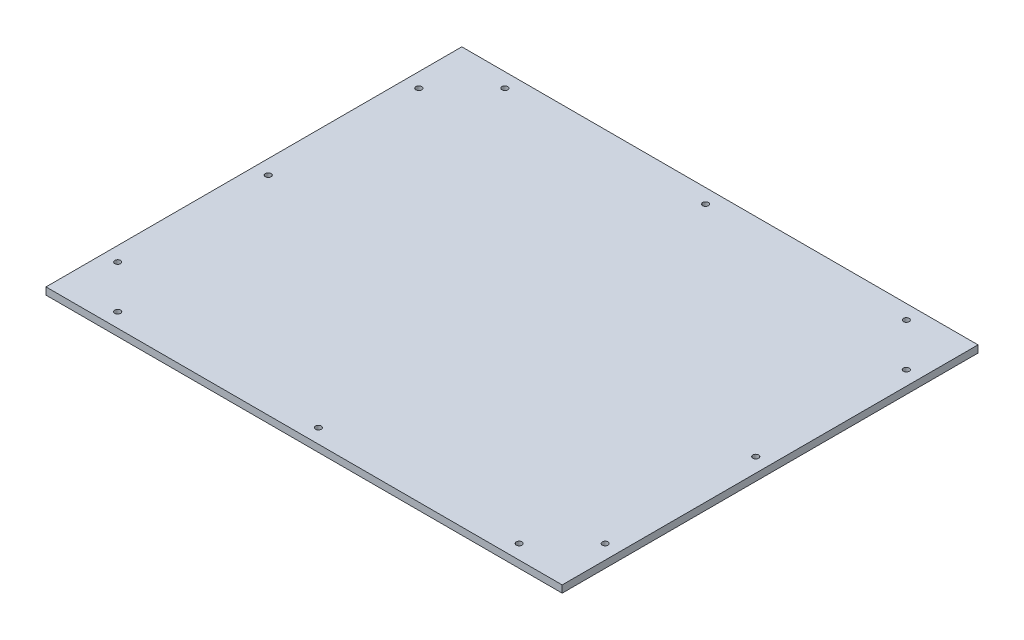
SolidWorks part; units mm, degrees
ref_plane "Front Plane" through (0, 0, 0) normal (0, 0, 1) x (1, 0, 0)
ref_plane "Top Plane" through (0, 0, 0) normal (0, 1, 0) x (1, 0, 0)
ref_plane "Right Plane" through (0, 0, 0) normal (1, 0, 0) x (0, 0, -1)
sketch "Sketch1" plane through (0, 0, 0) normal (0, 1, 0) x (1, 0, 0)
  line L0 (228.6, 368.3) -> (228.6, 0) construction
  line L1 (0, 0) -> (457.2, 0)
  line L2 (0, 0) -> (0, 368.3)
  line L3 (0, 368.3) -> (457.2, 368.3)
  line L4 (457.2, 0) -> (457.2, 368.3)
  line L6 (444.5, 12.7) -> (12.7, 12.7) construction
  line L7 (444.5, 12.7) -> (444.5, 355.6) construction
  line L8 (444.5, 355.6) -> (12.7, 355.6) construction
  line L9 (12.7, 12.7) -> (12.7, 355.6) construction
  line L10 (444.5, 12.7) -> (12.7, 355.6) construction
  line L11 (444.5, 355.6) -> (12.7, 12.7) construction
  circle A0 centre (50.8, 355.6) radius 2.5527
  circle A1 centre (406.4, 355.6) radius 2.5527
  circle A2 centre (406.4, 12.7) radius 2.5527
  circle A3 centre (50.8, 12.7) radius 2.5527
  circle A4 centre (228.6, 12.7) radius 2.5527
  circle A5 centre (228.6, 355.6) radius 2.5527
  circle A6 centre (12.7, 184.15) radius 2.5527
  circle A7 centre (444.5, 184.15) radius 2.5527
  circle A8 centre (12.7, 50.8) radius 2.5527
  circle A9 centre (444.5, 50.8) radius 2.5527
  circle A10 centre (444.5, 317.5) radius 2.5527
  circle A11 centre (12.7, 317.5) radius 2.5527
  point P7 (228.6, 184.15)
  dimension "D5" = 5.1054
  dimension "D6" = 5.1054
  dimension "D7" = 50.8
  dimension "D8" = 5.1054
  dimension "D9" = 5.1054
  dimension "D10" = 50.8
  dimension "D11" = 5.1054
  dimension "D12" = 5.1054
  dimension "D13" = 5.1054
  dimension "D15" = 5.1054
  dimension "D18" = 5.1054
  dimension "D19" = 5.1054
  dimension "D21" = 5.1054
  dimension "D23" = 5.1054
  dimension "D1" = 457.2
  dimension "D2" = 368.3
  dimension "D3" = 12.7
  dimension "D4" = 12.7
  dimension "D14" = 50.8
  dimension "D16" = 50.8
  dimension "D17" = 50.8
  dimension "D20" = 50.8
  dimension "D22" = 50.8
  dimension "D24" = 50.8
extrude "Boss-Extrude1" add sketch "Sketch1" along normal blind 6.35
